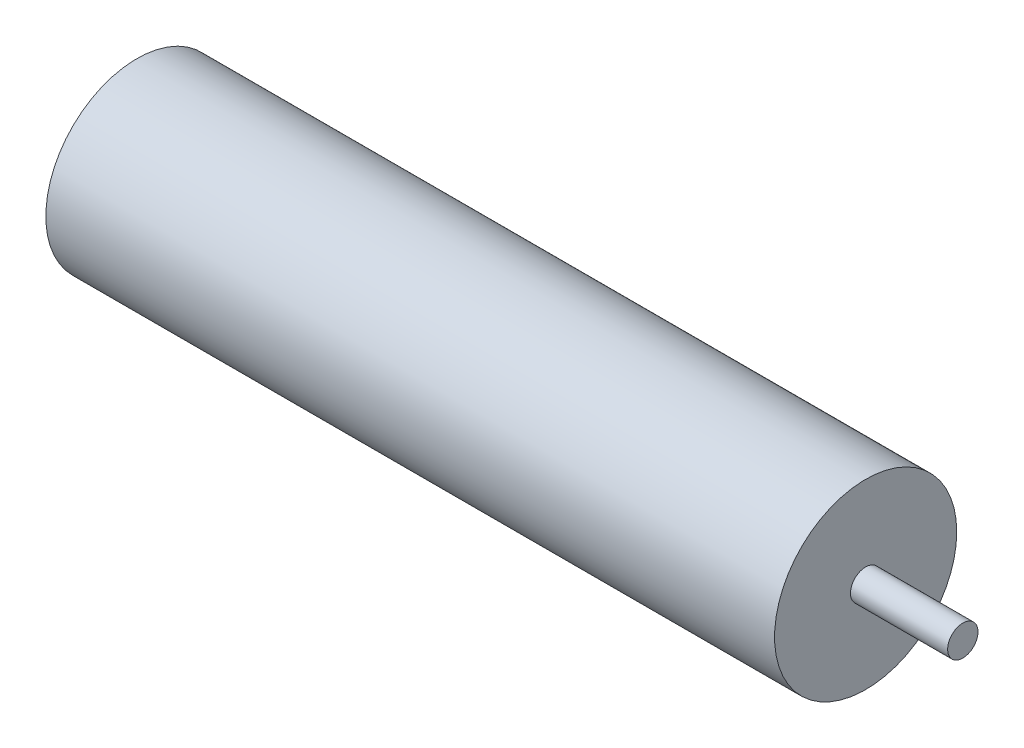
SolidWorks part; units mm, degrees
ref_plane "Front Plane" through (0, 0, 0) normal (0, 0, 1) x (1, 0, 0)
ref_plane "Top Plane" through (0, 0, 0) normal (0, 1, 0) x (1, 0, 0)
ref_plane "Right Plane" through (0, 0, 0) normal (1, 0, 0) x (0, 0, -1)
sketch "Sketch1" plane through (0, 0, 0) normal (1, 0, 0) x (0, 0, -1)
  circle A0 centre (0, 0) radius 15
  dimension "D1" = 30
extrude "Boss-Extrude1" add sketch "Sketch1" along normal blind 120
sketch "Sketch2" plane through (120, 0, 0) normal (1, 0, 0) x (0, 0, -1)
  circle A0 centre (0, 0) radius 2.5
extrude "Boss-Extrude2" add sketch "Sketch2" along normal blind 16
